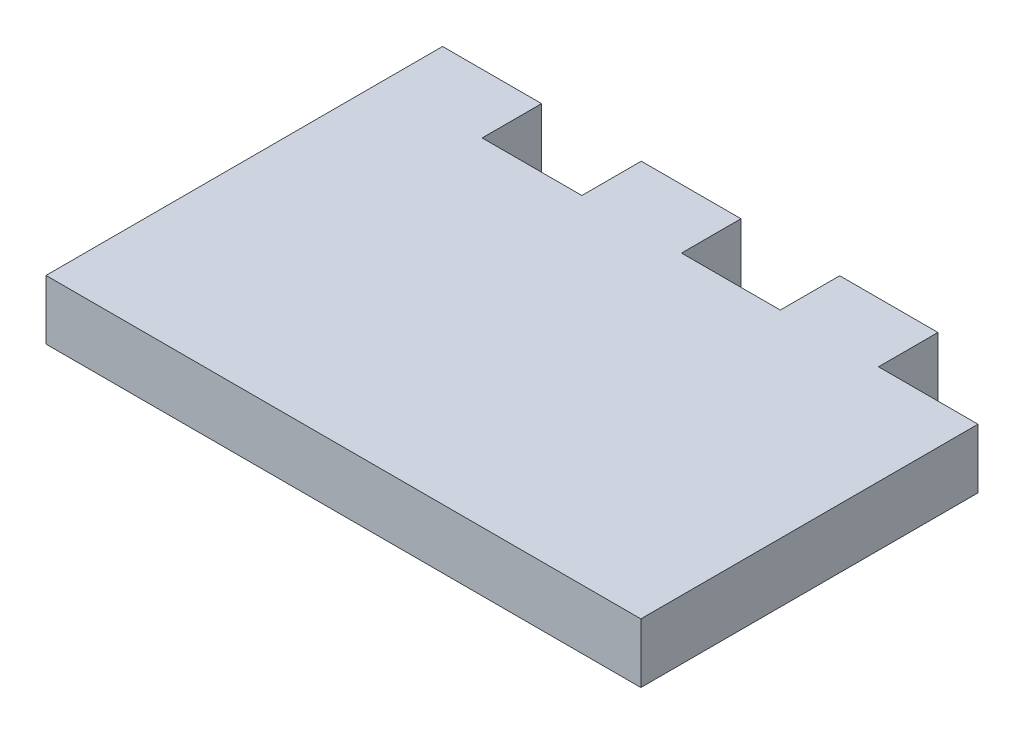
SolidWorks part; units mm, degrees
ref_plane "Front Plane" through (0, 0, 0) normal (0, 0, 1) x (1, 0, 0)
ref_plane "Top Plane" through (0, 0, 0) normal (0, 1, 0) x (1, 0, 0)
ref_plane "Right Plane" through (0, 0, 0) normal (1, 0, 0) x (0, 0, -1)
sketch "Sketch1" plane through (0, 0, 0) normal (0, 1, 0) x (1, 0, 0)
  line L1 (0, 0) -> (30, 0)
  line L2 (0, 0) -> (0, 20)
  line L3 (0, 20) -> (30, 20)
  line L4 (30, 0) -> (30, 20)
  dimension "D1" = 30
  dimension "D2" = 20
extrude "Boss-Extrude1" add sketch "Sketch1" along normal blind 3 contours L2 L1 L4 L3
sketch "Sketch2" plane through (0, 3, 0) normal (0, 1, 0) x (1, 0, 0)
  line L0 (30, 0) -> (30, 20) construction
  line L5 (4.9931, 20) -> (10.0211, 20)
  line L6 (4.9931, 20) -> (4.9931, 17.0024)
  line L7 (4.9931, 17.0024) -> (10.0211, 17.0024)
  line L8 (10.0211, 20) -> (10.0211, 17.0024)
  line L13 (15.0491, 20) -> (20.028, 20)
  line L14 (15.0491, 20) -> (15.0491, 17.0024)
  line L15 (15.0491, 17.0024) -> (20.028, 17.0024)
  line L16 (20.028, 20) -> (20.028, 17.0024)
  line L21 (24.9824, 20) -> (30, 20)
  line L22 (24.9824, 20) -> (24.9824, 17.0024)
  line L23 (24.9824, 17.0024) -> (30, 17.0024)
  line L24 (30, 20) -> (30, 17.0024)
  line M24 (30, 20) -> (0, 20)
  line M27 (30, 0) -> (30, 20)
extrude "Cut-Extrude1" cut sketch "Sketch2" against normal blind 3 contours L8 L6 L7 M24 | L16 L14 L15 M24 | L22 L23 M27 M24
